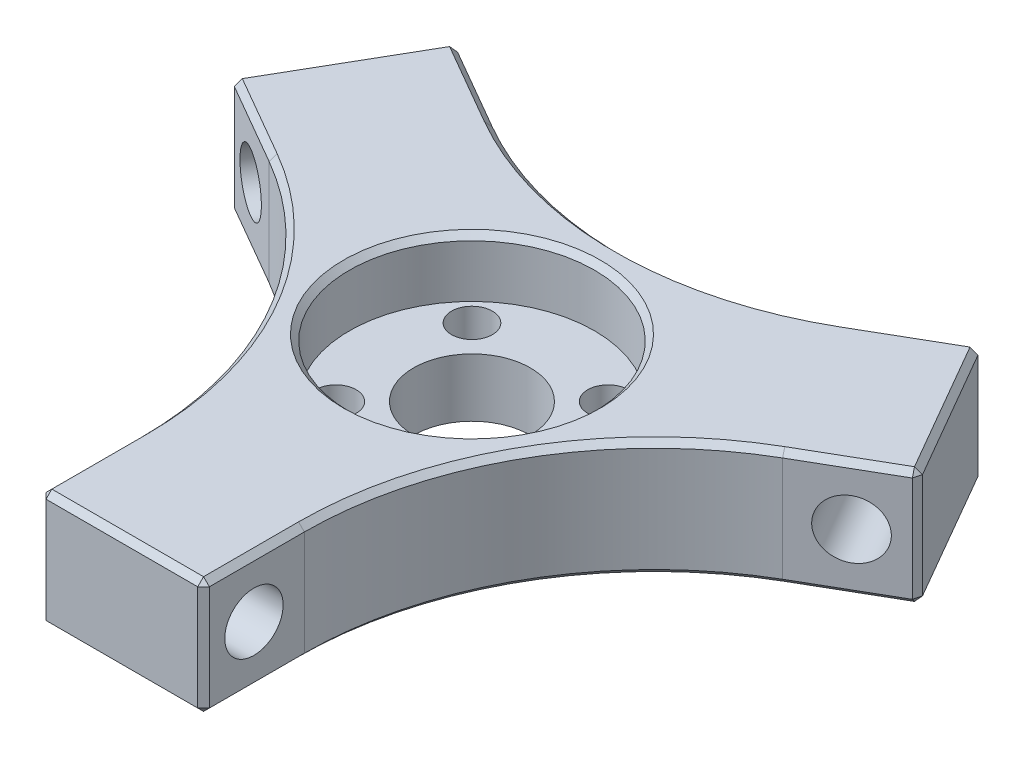
SolidWorks part; units mm, degrees
material "Mild Steel"
ref_plane "Front Plane" through (0, 0, 0) normal (0, 0, 1) x (1, 0, 0)
ref_plane "Top Plane" through (0, 0, 0) normal (0, 1, 0) x (1, 0, 0)
ref_plane "Right Plane" through (0, 0, 0) normal (1, 0, 0) x (0, 0, -1)
sketch "Sketch1" plane through (0, 0, 0) normal (0, 1, 0) x (1, 0, 0)
  line L0 (-25.9808, 15) -> (0, 0) construction
  line L1 (0, 60) -> (-51.9615, -30)
  line L2 (-51.9615, -30) -> (51.9615, -30)
  line L3 (51.9615, -30) -> (0, 60)
  line L4 (0, 0) -> (25.9808, 15) construction
  line L5 (0, 0) -> (0, -30) construction
  circle A0 centre (0, 0) radius 30 construction
  dimension "D1" = 30
sketch "Sketch2" plane through (0, 0, 0) normal (0, 1, 0) x (1, 0, 0)
  line L9 (-22.4808, 21.0622) -> (-29.4808, 8.9378)
  line L10 (0, -8.0829) -> (29.4808, 8.9378)
  line L11 (-29.4808, 8.9378) -> (0, -8.0829)
  line L12 (7, -4.0415) -> (29.4808, 8.9378)
  line L13 (-29.4808, 8.9378) -> (-7, -4.0415)
  line L14 (0, 8.0829) -> (22.4808, 21.0622)
  line L15 (-22.4808, 21.0622) -> (0, 8.0829)
  line L16 (0, 8.0829) -> (22.4808, 21.0622)
  line L17 (-22.4808, 21.0622) -> (0, 8.0829)
  line L18 (-7, 0) -> (-7, -30)
  line L19 (-7, -4.0415) -> (-7, -30)
  line L20 (7, 0) -> (7, -30)
  line L21 (7, -4.0415) -> (7, -30)
  line L22 (-7, -30) -> (7, -30)
  line L23 (29.4808, 8.9378) -> (22.4808, 21.0622)
  dimension "D1" = 7
  dimension "D2" = 7
  dimension "D3" = 7
  dimension "D4" = 7
extrude "Boss-Extrude1" add sketch "Sketch2" along normal blind 10
sketch "Sketch8" plane through (0, 10, 0) normal (0, 1, 0) x (1, 0, 0)
  circle A0 centre (0, 0) radius 5
  dimension "D1" = 10
extrude "Cut-Extrude1" cut sketch "Sketch8" against normal through all
fillet "Fillet1" radius 30 3 edges at (7, 5, 4.0415) (-7, 5, 4.0415) (0, 5, -8.0829)
hole_wizard "M6x1.0 Tapped Hole1" positions "Sketch17" profile "Sketch18" tap size "M6x1.0" standard "ANSI Metric" end condition up to next
sketch "Sketch17" plane through (-3.5, 0, -6.0622) normal (-0.5, 0, -0.866) x (-0.866, 0, 0.5)
  line L0 (-30, 10) -> (-21.362, 0) construction
  point P0 (-25.681, 5)
sketch "Sketch18" plane through (18.7404, 5, -18.9027) normal (0, 1, 0) x (-0.866, 0, 0.5)
  line L0 (0, 0) -> (0, 14)
  line L1 (0, 14) -> (2.5, 14)
  line L2 (2.5, 14) -> (2.5, 0)
  line L5 (2.5, 0) -> (0, 0)
  line L11 (0, -6.35) -> (0, 107.95) construction
  dimension "Thru Tap Drill Dia." = 5
  dimension "Thru Tap Drill Depth" = 14
cosmetic thread "Hole Thread25" parameters "D2"=6
hole_wizard "M6x1.0 Tapped Hole2" positions "Sketch19" profile "Sketch20" tap size "M6x1.0" standard "ANSI Metric" end condition up to next
sketch "Sketch19" plane through (3.5, 0, -6.0622) normal (0.5, 0, -0.866) x (-0.866, 0, -0.5)
  line L0 (21.362, 10) -> (30, 0) construction
  point P0 (25.681, 5)
sketch "Sketch20" plane through (-18.7404, 5, -18.9027) normal (0, 1, 0) x (-0.866, 0, -0.5)
  line L0 (0, 0) -> (0, 14)
  line L1 (0, 14) -> (2.5, 14)
  line L2 (2.5, 14) -> (2.5, 0)
  line L5 (2.5, 0) -> (0, 0)
  line L11 (0, -6.35) -> (0, 107.95) construction
  dimension "Thru Tap Drill Dia." = 5
  dimension "Thru Tap Drill Depth" = 14
cosmetic thread "Hole Thread26" parameters "D2"=6
hole_wizard "M6x1.0 Tapped Hole3" positions "Sketch21" profile "Sketch22" tap size "M6x1.0" standard "ANSI Metric" end condition up to next
sketch "Sketch21" plane through (7, 0, 0) normal (1, 0, 0) x (0, 0, -1)
  line L0 (-21.362, 10) -> (-30, 0) construction
  point P0 (-25.681, 5)
sketch "Sketch22" plane through (7, 5, 25.681) normal (0, 1, 0) x (0, 0, -1)
  line L0 (0, 0) -> (0, 14)
  line L1 (0, 14) -> (2.5, 14)
  line L2 (2.5, 14) -> (2.5, 0)
  line L5 (2.5, 0) -> (0, 0)
  line L11 (0, -6.35) -> (0, 107.95) construction
  dimension "Thru Tap Drill Dia." = 5
  dimension "Thru Tap Drill Depth" = 14
cosmetic thread "Hole Thread27" parameters "D2"=6
hole_wizard "M3 Clearance Hole2" positions "Sketch26" profile "Sketch25" hole size "M3" standard "ANSI Metric"
sketch "Sketch26" plane through (0, 10, 0) normal (0, 1, 0) x (1, 0, 0)
  line L0 (0, 0) -> (5.8336, 5.8336) construction
  line L3 (0, 0) -> (0, 8.25) construction
  circle A0 centre (0, 0) radius 8.25 construction
  point P4 (5.8336, 5.8336)
  point P32 (5.8336, -5.8336)
  point P33 (-5.8336, -5.8336)
  point P34 (-5.8336, 5.8336)
  point P35 (0, 0)
  dimension "D1" = 16.5
  dimension "D2" = 45
  dimension "D3" = 4
sketch "Sketch25" plane through (5.8336, 10, -5.8336) normal (1, 0, 0) x (0, 0, 1)
  line L0 (0, 0) -> (0, 13.1515)
  line L1 (0, 13.1515) -> (1.75, 12.1)
  line L2 (1.75, 12.1) -> (1.75, 0)
  line L5 (1.75, 0) -> (0, 0)
  line L10 (0, 13.1515) -> (-1.75, 12.1) construction
  line L11 (0, -6.35) -> (0, 107.95) construction
  dimension "Hole Dia." = 3.5
  dimension "Hole Depth" = 12.1
  dimension "Drill Angle" = 118
hole_wizard "Ø3.0mm Dowel Hole2" positions "Sketch27" profile "Sketch28" hole size "Ø3.0" standard "ANSI Metric"
sketch "Sketch27" plane through (0, 10, 0) normal (0, 1, 0) x (1, 0, 0)
  circle A0 centre (0, 0) radius 8.25 construction
  point P0 (0, -8.25)
sketch "Sketch28" plane through (0, 10, 8.25) normal (1, 0, 0) x (0, 0, 1)
  line L0 (0, 0) -> (0, 13.0013)
  line L1 (0, 13.0013) -> (1.5, 12.1)
  line L2 (1.5, 12.1) -> (1.5, 0)
  line L5 (1.5, 0) -> (0, 0)
  line L10 (0, 13.0013) -> (-1.5, 12.1) construction
  line L11 (0, -6.35) -> (0, 107.95) construction
  dimension "Hole Dia." = 3
  dimension "Hole Depth" = 12.1
  dimension "Drill Angle" = 118
sketch "Sketch29" plane through (0, 10, 0) normal (0, 1, 0) x (1, 0, 0)
  circle A0 centre (0, 0) radius 10.5
  dimension "D1" = 21
extrude "Cut-Extrude2" cut sketch "Sketch29" against normal blind 5
chamfer "Chamfer2" distance 0.5 angle 45 31 edges at (0, 10, -12.7239) (0, 0, -12.7239) (-11.0192, 10, 6.362) (-22.4808, 5, -21.0622) (-25.7404, 10, -6.7783) (-18.7404, 10, -18.9027) (-25.9808, 10, -15) (-29.4808, 5, -8.9378) (-18.7404, 0, -18.9027) (-25.9808, 0, -15) (-25.7404, 0, -6.7783) (-11.0192, 0, 6.362) (11.0192, 10, 6.362) (29.4808, 5, -8.9378) (18.7404, 10, -18.9027) (25.7404, 10, -6.7783) (25.9808, 10, -15) (22.4808, 5, -21.0622) (18.7404, 0, -18.9027) (25.9808, 0, -15) (25.7404, 0, -6.7783) (11.0192, 0, 6.362) (-7, 5, 30) (7, 10, 25.681) (-7, 10, 25.681) (0, 10, 30) (7, 5, 30) (7, 0, 25.681) (0, 0, 30) (-7, 0, 25.681) (0, 10, 10.5)
